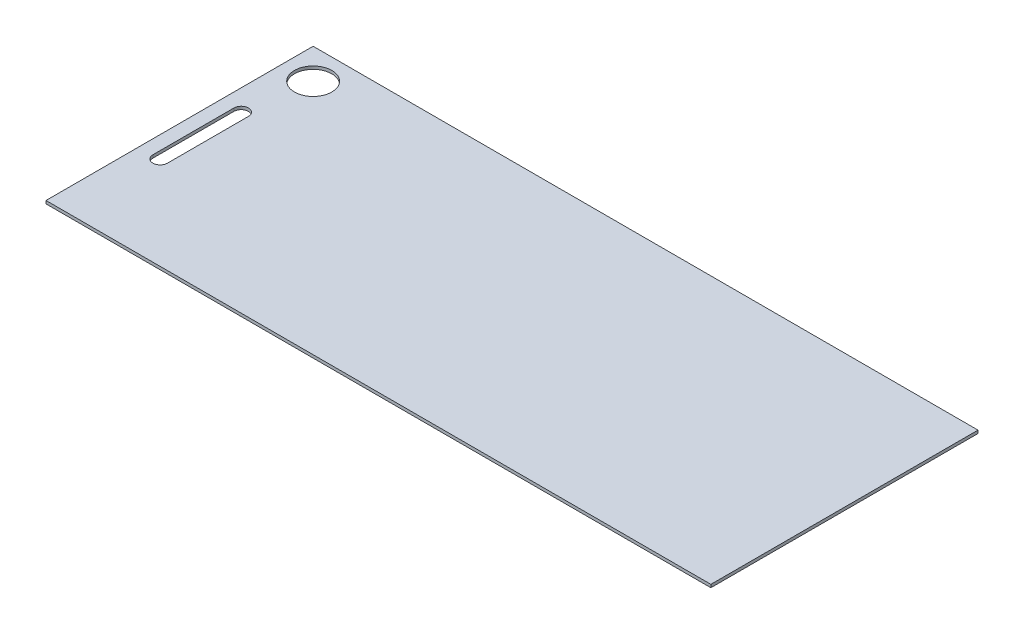
SolidWorks part; units mm, degrees
ref_plane "Front Plane" through (0, 0, 0) normal (0, 0, 1) x (1, 0, 0)
ref_plane "Top Plane" through (0, 0, 0) normal (0, 1, 0) x (1, 0, 0)
ref_plane "Right Plane" through (0, 0, 0) normal (1, 0, 0) x (0, 0, -1)
sketch "Sketch1" plane through (0, 0, 0) normal (0, 1, 0) x (1, 0, 0)
  line L1 (-853.44, 342.9) -> (853.44, 342.9)
  line L2 (-853.44, 342.9) -> (-853.44, -342.9)
  line L3 (-853.44, -342.9) -> (853.44, -342.9)
  line L4 (853.44, 342.9) -> (853.44, -342.9)
  line L5 (-853.44, 342.9) -> (853.44, -342.9) construction
  line L6 (-853.44, -342.9) -> (853.44, 342.9) construction
  point P0 (0, 0)
  dimension "D1" = 685.8
  dimension "D2" = 1706.88
extrude "Boss-Extrude1" add sketch "Sketch1" along normal blind 7.62
sketch "Sketch2" plane through (0, 7.62, 0) normal (0, 1, 0) x (1, 0, 0)
  line L0 (-799.1763, 103.9808) -> (-799.1763, -103.9808) construction
  line L1 (-780.4938, 103.9808) -> (-780.4938, -103.9808)
  line L2 (-817.8588, 103.9808) -> (-817.8588, -103.9808)
  line L3 (-853.44, 342.9) -> (-640.5008, 129.9608) construction
  arc A0 (-780.4938, 103.9808) -> (-817.8588, 103.9808) centre (-799.1763, 103.9808) ccw
  arc A1 (-817.8588, -103.9808) -> (-780.4938, -103.9808) centre (-799.1763, -103.9808) ccw
  circle A2 centre (-775.6989, 265.1589) radius 48.0031
  point P2 (-799.1763, 0)
  point P10 (0, 0)
extrude "Cut-Extrude1" cut sketch "Sketch2" against normal blind 7.62
